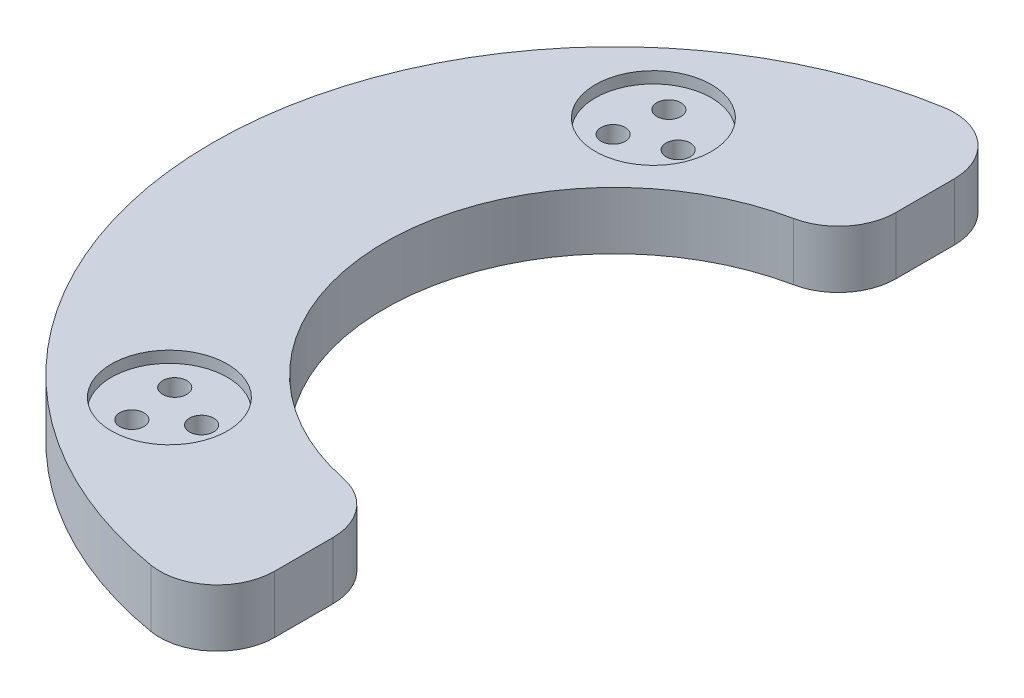
SolidWorks part; units mm, degrees
ref_plane "前视基准面" through (0, 0, 0) normal (0, 0, 1) x (1, 0, 0)
ref_plane "上视基准面" through (0, 0, 0) normal (0, 1, 0) x (1, 0, 0)
ref_plane "右视基准面" through (0, 0, 0) normal (1, 0, 0) x (0, 0, -1)
sketch "草图1" plane through (0, 0, 0) normal (0, 1, 0) x (1, 0, 0)
  line L0 (0, -55) -> (0, 55) construction
  line L1 (0, 0) -> (-35.3533, -42.1324) construction
  line L2 (0, 0) -> (-55, 0) construction
  circle A1 centre (0, 0) radius 45 construction
  circle A2 centre (-35.3533, -42.1324) radius 10 construction
  circle A3 centre (0, 0) radius 40
  circle A4 centre (0, 0) radius 70
  dimension "D1" = 90
  dimension "D2" = 25
  dimension "D4" = 20
  dimension "D3" = 40
  dimension "D5" = 5
extrude "凸台-拉伸1" add sketch "草图1" along normal blind 10
sketch "草图2" plane through (0, 10, 0) normal (0, 1, 0) x (1, 0, 0)
  line L1 (0, -155.5267) -> (120.3314, -155.5267)
  line L2 (0, -155.5267) -> (0, 172.5015)
  line L3 (0, 172.5015) -> (120.3314, 172.5015)
  line L4 (120.3314, -155.5267) -> (120.3314, 172.5015)
extrude "切除-拉伸1" cut sketch "草图2" against normal blind 62
sketch "草图3" plane through (0, 10, 0) normal (0, 1, 0) x (1, 0, 0)
  line L0 (0, 0) -> (-44.9951, -53.6231) construction
  line L1 (0, -40) -> (0, -70) construction
  line L2 (0, 55) -> (-61.9974, 55) construction
  line L3 (0, 70) -> (0, 40) construction
  arc A0 (0, 70) -> (0, -70) centre (0, 0) ccw construction
  circle A2 centre (0, 0) radius 40 construction
  circle A3 centre (0, 0) radius 70 construction
  circle A4 centre (0, 0) radius 55 construction
  circle A5 centre (-35.3533, -42.1324) radius 10.1
  dimension "D2" = 20.2
  dimension "D1" = 40
extrude "切除-拉伸2" cut sketch "草图3" against normal blind 2
mirror "镜向1" about plane through (0, 0, 0) normal (0, 0, 1) of "切除-拉伸2"
fillet "圆角1" radius 10 4 edges at (0, 5, -70) (0, 5, 70) (0, 5, -40) (0, 5, 40)
sketch "草图4" plane through (0, 8, 0) normal (0, 1, 0) x (1, 0, 0)
  line L1 (-38.3911, -38.161) -> (-37.2738, -46.7489) construction
  line L2 (-37.2738, -46.7489) -> (-30.3951, -41.4874) construction
  line L3 (-30.3951, -41.4874) -> (-38.3911, -38.161) construction
  circle A0 centre (-35.3533, -42.1324) radius 5 construction
  circle A1 centre (-38.3911, -38.161) radius 2.1
  circle A2 centre (-30.3951, -41.4874) radius 2.1
  circle A3 centre (-37.2738, -46.7489) radius 2.1
  dimension "D1" = 10
  dimension "D2" = 4.2
extrude "切除-拉伸3" cut sketch "草图4" against normal blind 10
mirror "镜向2" about plane through (0, 0, 0) normal (0, 0, 1) of "切除-拉伸3"
